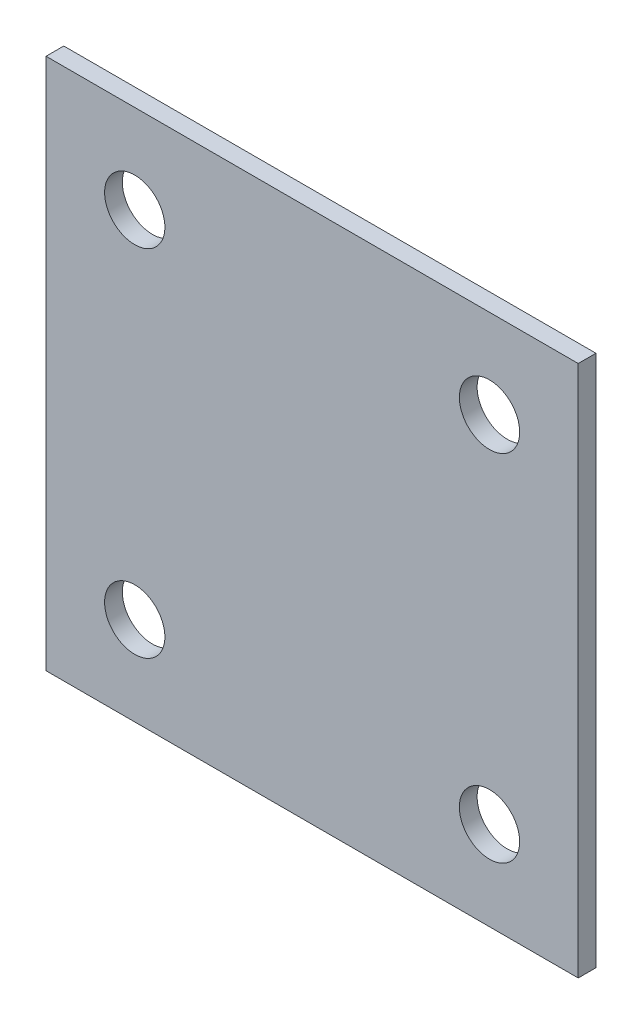
SolidWorks part; units mm, degrees
ref_plane "Plan de face" through (0, 0, 0) normal (0, 0, 1) x (1, 0, 0)
ref_plane "Plan de dessus" through (0, 0, 0) normal (0, 1, 0) x (1, 0, 0)
ref_plane "Plan de droite" through (0, 0, 0) normal (1, 0, 0) x (0, 0, -1)
sketch "Esquisse1" plane through (0, 0, 0) normal (0, 0, 1) x (1, 0, 0)
  line L1 (15, -15) -> (-15, -15)
  line L2 (15, -15) -> (15, 15)
  line L3 (15, 15) -> (-15, 15)
  line L4 (-15, -15) -> (-15, 15)
  line L5 (15, -15) -> (-15, 15) construction
  line L6 (15, 15) -> (-15, -15) construction
  point P0 (0, 0)
  dimension "D1" = 30
  dimension "D2" = 30
extrude "Boss.-Extru.1" add sketch "Esquisse1" along normal blind 1
hole_wizard "Dégagement M31" positions "Esquisse2" profile "Esquisse3" hole size "M3" standard "DIN" end condition through all
sketch "Esquisse2" plane through (0, 0, 0) normal (0, 0, -1) x (-1, 0, 0)
  point P0 (10, -10)
  point P2 (10, 10)
  point P4 (-10, 10)
  point P6 (-10, -10)
  dimension "D1" = 20
  dimension "D2" = 20
  dimension "D3" = 10
  dimension "D4" = 10
sketch "Esquisse3" plane through (-10, -10, 0) normal (1, 0, 0) x (0, 1, 0)
  line L0 (0, 0) -> (0, 1)
  line L1 (0, 1) -> (1.7, 1)
  line L2 (1.7, 1) -> (1.7, 0)
  line L5 (1.7, 0) -> (0, 0)
  line L11 (0, -6.35) -> (0, 107.95) construction
  dimension "Diamètre du perçage jusqu'au prochain" = 3.4
  dimension "Profondeur du perçage jusqu'au prochain" = 1
equation "\"d\"= 20mm"
equation "\"D1@Esquisse2\"=\"d\""
equation "\"D2@Esquisse2\"=\"d\""
equation "\"D3@Esquisse2\"=\"d\"/2"
equation "\"D4@Esquisse2\"=\"d\"/2"
